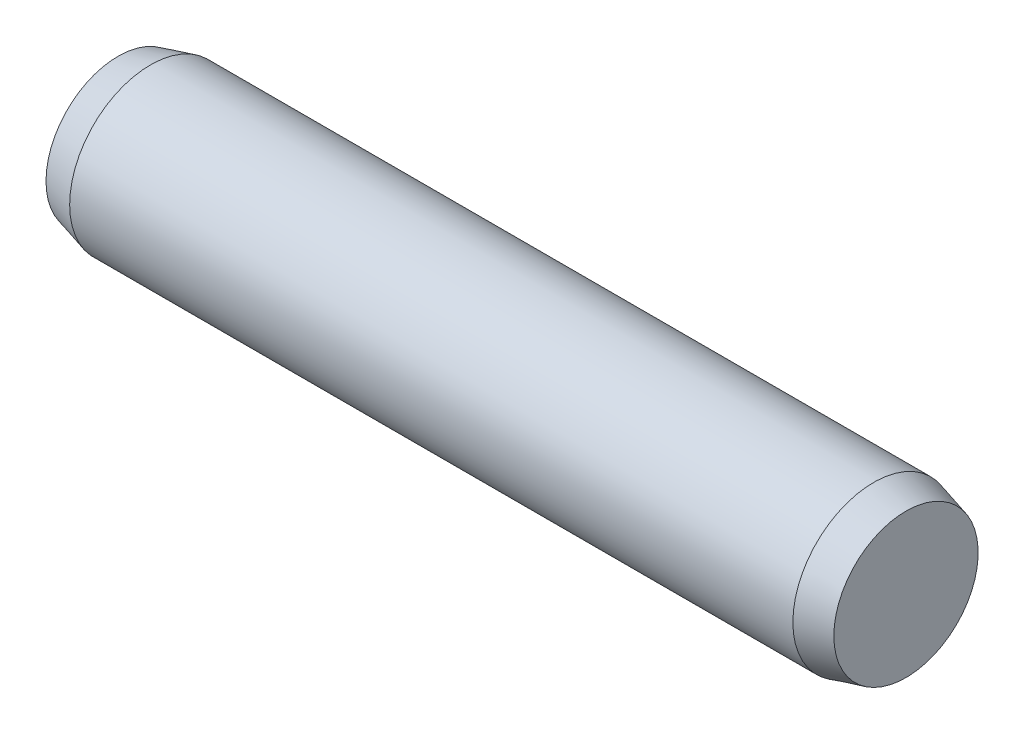
SolidWorks part; units mm, degrees
ref_plane "Plane1" through (0, 0, 0) normal (0, 0, 1) x (1, 0, 0)
ref_plane "Plane2" through (0, 0, 0) normal (0, 1, 0) x (1, 0, 0)
ref_plane "Plane3" through (0, 0, 0) normal (1, 0, 0) x (0, 0, -1)
sketch "Sketch1" plane through (0, 0, 0) normal (0, 0, 1) x (1, 0, 0)
  line L1 (-6.35, 0) -> (107.95, 0) construction
  line L2 (0, 0) -> (39, 0)
  line L3 (39, 0) -> (39, 3.5713)
  line L4 (39, 3.5713) -> (37.4, 4)
  line L5 (37.4, 4) -> (1.6, 4)
  line L6 (0, 3.5713) -> (0, 0)
  line L7 (0, 3.5713) -> (1.6, 4)
  dimension "Chamfer_len" = 1.6
  dimension "D3" = 15
  dimension "Diameter" = 8
  dimension "D1" = 1.6
  dimension "D2" = 15
  dimension "Length" = 39
revolve "Base-Revolve" add sketch "Sketch1" angle 360 about L1
equation "\"D3@Sketch1\" = 15.0"
equation "\"D1@Sketch1\" = \"Chamfer_len@Sketch1\""
equation "\"D2@Sketch1\" = \"D3@Sketch1\""
